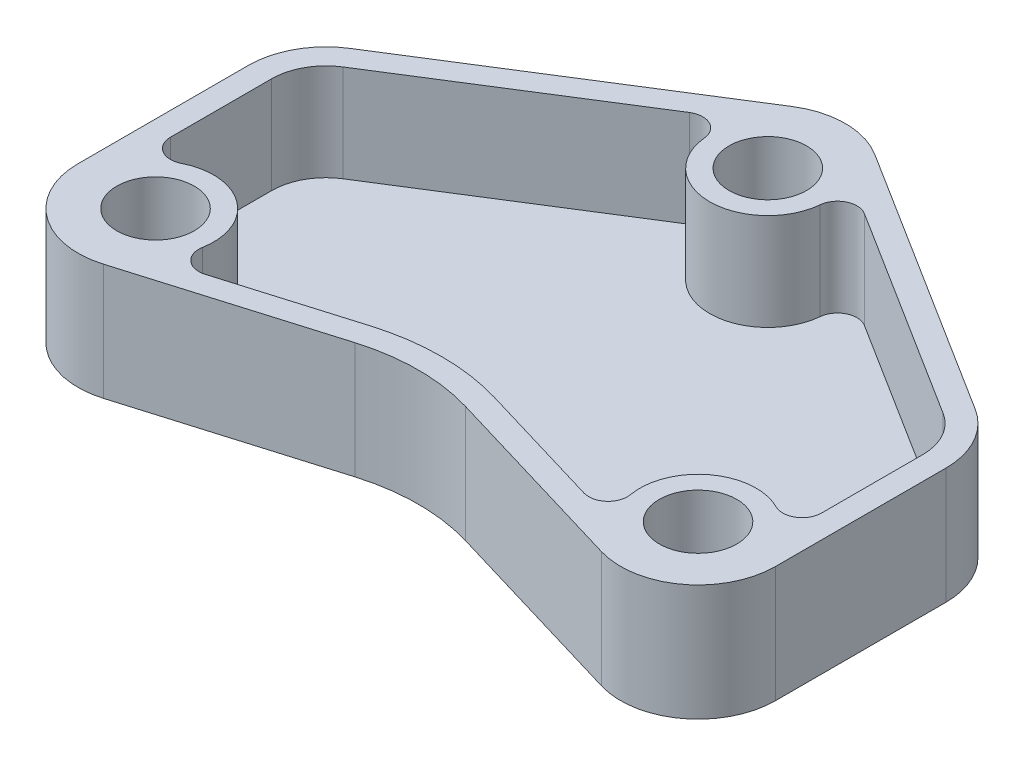
SolidWorks part; units mm, degrees
ref_plane "Front Plane" through (0, 0, 0) normal (0, 0, 1) x (1, 0, 0)
ref_plane "Top Plane" through (0, 0, 0) normal (0, 1, 0) x (1, 0, 0)
ref_plane "Right Plane" through (0, 0, 0) normal (1, 0, 0) x (0, 0, -1)
sketch "Sketch1" plane through (0, 0, 0) normal (0, 1, 0) x (1, 0, 0)
  line L0 (0, 0) -> (0, 77.8018) construction
  line L1 (-90, 0) -> (-90, 43.9546)
  line L2 (-80.6513, 60.8824) -> (-10.6513, 104.9278)
  line L3 (90, 0) -> (90, 43.9546)
  line L4 (80.6513, 60.8824) -> (10.6513, 104.9278)
  line L5 (-64.2857, -19.1663) -> (-14.2857, -4.2592)
  line L6 (14.2857, -4.2592) -> (64.2857, -19.1663)
  arc A0 (10.6513, 104.9278) -> (-10.6513, 104.9278) centre (0, 88) ccw
  circle A1 centre (0, 88) radius 10
  arc A2 (-90, 0) -> (-64.2857, -19.1663) centre (-70, 0) ccw
  circle A3 centre (-70, 0) radius 10
  circle A4 centre (70, 0) radius 10
  arc A5 (90, 0) -> (64.2857, -19.1663) centre (70, 0) cw
  arc A6 (14.2857, -4.2592) -> (-14.2857, -4.2592) centre (0, -52.1749) ccw
  arc A7 (90, 43.9546) -> (80.6513, 60.8824) centre (70, 43.9546) ccw
  arc A8 (-90, 43.9546) -> (-80.6513, 60.8824) centre (-70, 43.9546) cw
  point P25 (90, 55)
  point P28 (-90, 55)
  dimension "D1" = 40
  dimension "D2" = 20
  dimension "D6" = 50
  dimension "D7" = 20
  dimension "D3" = 140
  dimension "D4" = 88
  dimension "D5" = 55
extrude "Boss-Extrude1" add sketch "Sketch1" along normal blind 30
sketch "Sketch2" plane through (0, 30, 0) normal (0, 1, 0) x (1, 0, 0)
  line L2 (-7.4559, 99.8494) -> (-77.4559, 55.8041)
  line L3 (-12.0139, 96.9815) -> (-77.4559, 55.8041)
  line L4 (-66, -13.4164) -> (-16, 1.4907)
  line L5 (-84, 43.9546) -> (-84, 0)
  line L6 (-84, 43.9546) -> (-84, 5.3852)
  line L7 (-60.8393, -11.8778) -> (-16, 1.4907)
  line L15 (16, 1.4907) -> (66, -13.4164)
  line L16 (16, 1.4907) -> (60.8393, -11.8778)
  line L18 (84, 0) -> (84, 43.9546)
  line L19 (84, 5.3852) -> (84, 43.9546)
  line L21 (77.4559, 55.8041) -> (7.4559, 99.8494)
  line L22 (77.4559, 55.8041) -> (12.0139, 96.9815)
  arc A0 (-12.0139, 96.9815) -> (12.0139, 96.9815) centre (0, 88) ccw
  arc A1 (-60.8393, -11.8778) -> (-84, 5.3852) centre (-70, 0) ccw
  arc A2 (84, 5.3852) -> (60.8393, -11.8778) centre (70, 0) ccw
  arc A5 (-77.4559, 55.8041) -> (-84, 43.9546) centre (-70, 43.9546) ccw
  arc A6 (-77.4559, 55.8041) -> (-84, 43.9546) centre (-70, 43.9546) ccw
  arc A14 (16, 1.4907) -> (-16, 1.4907) centre (0, -52.1749) ccw
  arc A15 (16, 1.4907) -> (-16, 1.4907) centre (0, -52.1749) ccw
  arc A17 (84, 43.9546) -> (77.4559, 55.8041) centre (70, 43.9546) ccw
  arc A18 (84, 43.9546) -> (77.4559, 55.8041) centre (70, 43.9546) ccw
  point P4 (-90.5441, 55.8041)
  dimension "D1" = 30
  dimension "D2" = 6
  dimension "D3" = 6
  dimension "D4" = 6
  dimension "D5" = 6
  dimension "D6" = 6
  dimension "D7" = 6
  dimension "D8" = 6
  dimension "D9" = 6
  dimension "D10" = 6
extrude "Cut-Extrude1" cut sketch "Sketch2" against normal blind 25
fillet "Fillet1" radius 5 6 edges at (84, 17.5, -5.3852) (60.8393, 17.5, 11.8778) (-60.8393, 17.5, 11.8778) (-84, 17.5, -5.3852) (-12.0139, 17.5, -96.9815) (12.0139, 17.5, -96.9815)
